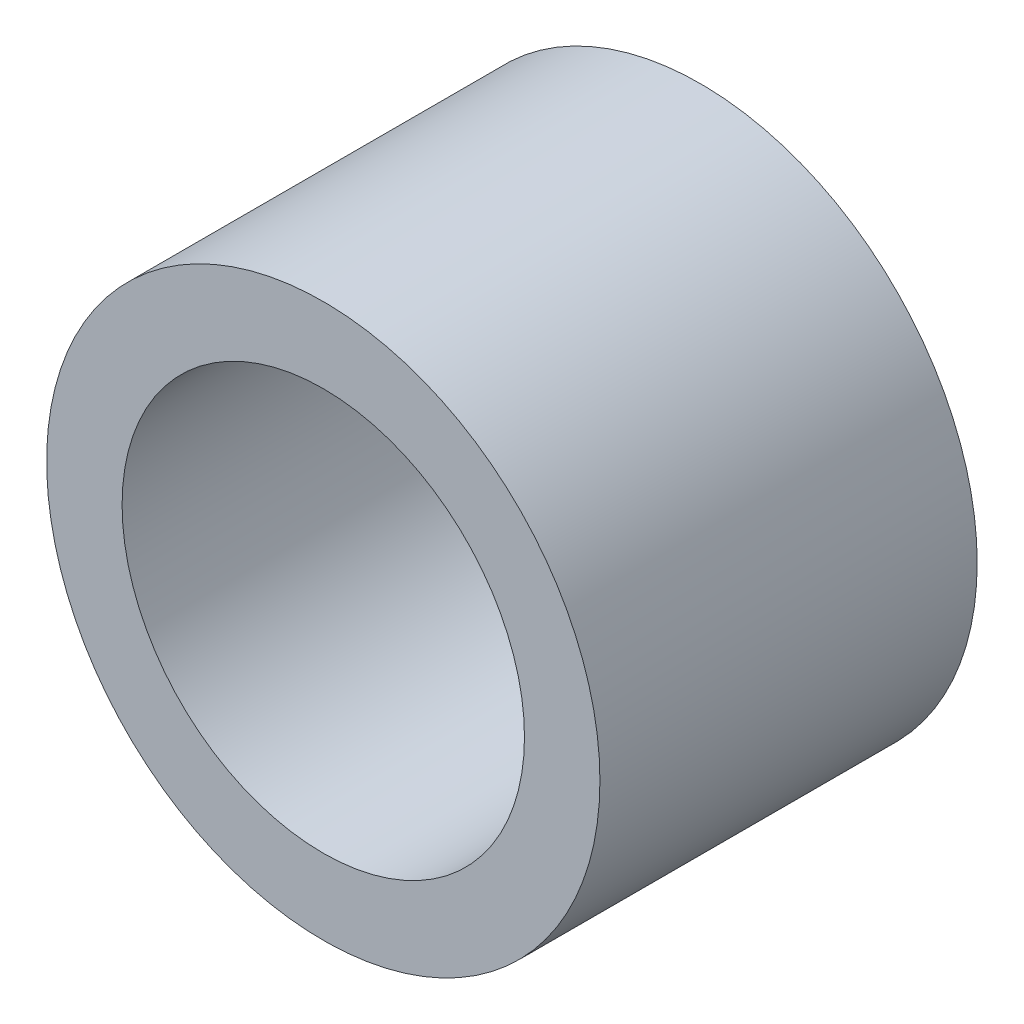
SolidWorks part; units mm, degrees
material "铜"
ref_plane "前基準面" through (0, 0, 0) normal (0, 0, 1) x (1, 0, 0)
ref_plane "上基準面" through (0, 0, 0) normal (0, 1, 0) x (1, 0, 0)
ref_plane "右基準面" through (0, 0, 0) normal (1, 0, 0) x (0, 0, -1)
sketch "草图1" plane through (0, 0, 0) normal (0, 0, 1) x (1, 0, 0)
  circle A0 centre (0, 0) radius 11
  circle A1 centre (0, 0) radius 8
  dimension "D1" = 22
  dimension "D2" = 16
extrude "凸台-拉伸1" add sketch "草图1" along normal blind 15
